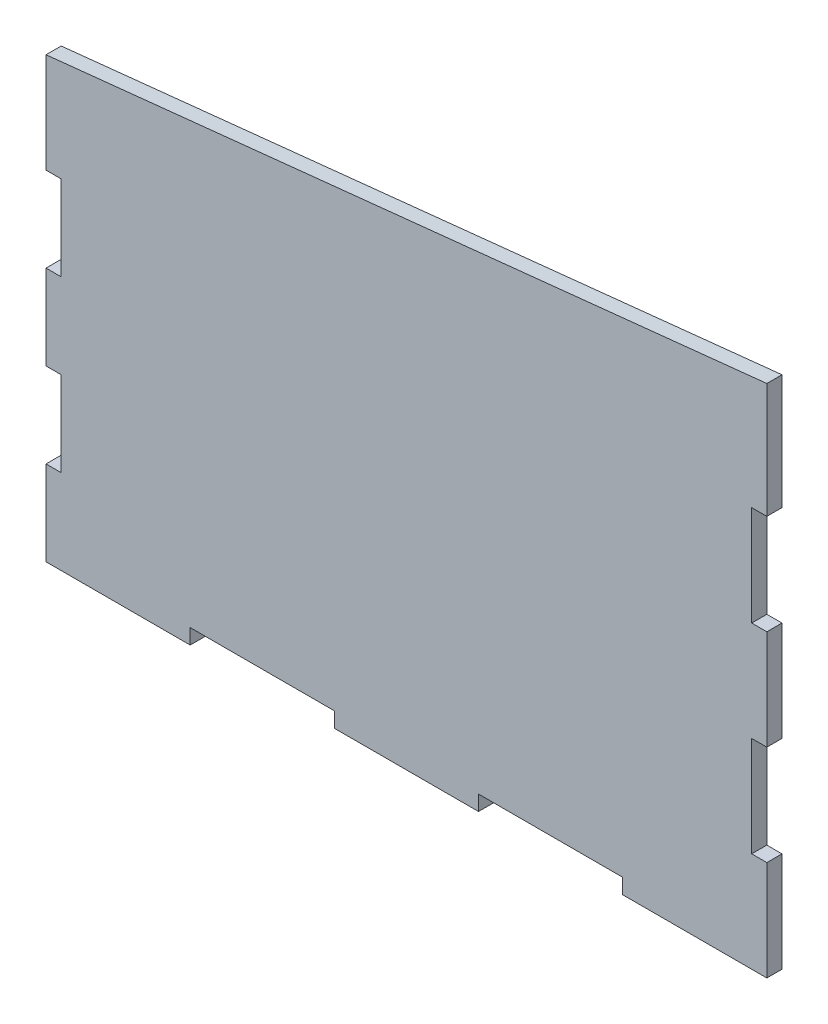
SolidWorks part; units mm, degrees
ref_plane "Plan de face" through (0, 0, 0) normal (0, 0, 1) x (1, 0, 0)
ref_plane "Plan de dessus" through (0, 0, 0) normal (0, 1, 0) x (1, 0, 0)
ref_plane "Plan de droite" through (0, 0, 0) normal (1, 0, 0) x (0, 0, -1)
sketch "Esquisse1" plane through (0, 0, 0) normal (0, 0, 1) x (1, 0, 0)
  line L0 (0, 0) -> (0, 145)
  line L1 (0, 145) -> (238, 170)
  line L2 (238, 170) -> (238, 5)
  line L3 (238, 5) -> (238, 0)
  line L4 (238, 0) -> (0, 0)
  point P5 (0, 0)
  dimension "D1" = 145
  dimension "D2" = 165
  dimension "D3" = 5
  dimension "D4" = 238
extrude "Boss.-Extru.1" add sketch "Esquisse1" along normal blind 5
sketch "Esquisse2" plane through (0, 0, 5) normal (0, 0, 1) x (1, 0, 0)
  line L0 (0, 145) -> (0, 0) construction
  line L1 (0, 28) -> (5, 28)
  line L2 (0, 28) -> (0, 56)
  line L3 (0, 56) -> (5, 56)
  line L4 (5, 28) -> (5, 56)
  line L6 (0, 84) -> (5, 84)
  line L7 (0, 84) -> (0, 112)
  line L8 (0, 112) -> (5, 112)
  line L9 (5, 84) -> (5, 112)
  line L10 (0, 0) -> (238, 0) construction
  line L11 (47.6, 0) -> (95.2, 0)
  line L12 (47.6, 0) -> (47.6, 5)
  line L13 (47.6, 5) -> (95.2, 5)
  line L14 (95.2, 0) -> (95.2, 5)
  line L16 (142.8, 0) -> (190.4, 0)
  line L17 (142.8, 0) -> (142.8, 5)
  line L18 (142.8, 5) -> (190.4, 5)
  line L19 (190.4, 0) -> (190.4, 5)
  line L20 (238, 0) -> (238, 170) construction
  line L21 (238, 132) -> (233, 132)
  line L22 (238, 132) -> (238, 99)
  line L23 (238, 99) -> (233, 99)
  line L24 (233, 132) -> (233, 99)
  line L26 (233, 33) -> (238, 33)
  line L27 (233, 33) -> (233, 66)
  line L28 (233, 66) -> (238, 66)
  line L29 (238, 33) -> (238, 66)
  dimension "D1" = 5
  dimension "D2" = 28
  dimension "D3" = 28
  dimension "D4" = 28
  dimension "D5" = 28
  dimension "D6" = 5
  dimension "D7" = 47.6
  dimension "D8" = 47.6
  dimension "D9" = 47.6
  dimension "D10" = 47.6
  dimension "D11" = 5
  dimension "D12" = 33
  dimension "D13" = 33
  dimension "D14" = 33
  dimension "D15" = 33
extrude "Enlèv. mat.-Extru.1" cut sketch "Esquisse2" against normal blind 5
